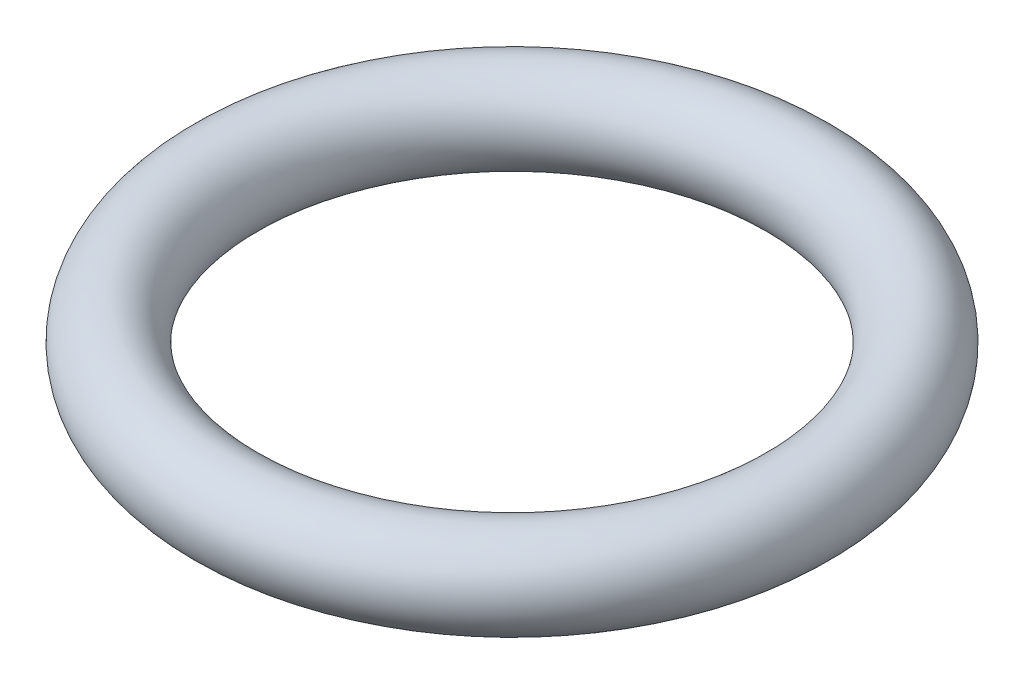
SolidWorks part; units mm, degrees
ref_plane "Front Plane" through (0, 0, 0) normal (0, 0, 1) x (1, 0, 0)
ref_plane "Top Plane" through (0, 0, 0) normal (0, 1, 0) x (1, 0, 0)
ref_plane "Right Plane" through (0, 0, 0) normal (1, 0, 0) x (0, 0, -1)
sketch "Sketch1" plane through (0, 0, 0) normal (0, 0, 1) x (1, 0, 0)
  line L0 (0, -3.9721) -> (0, 8.9728) construction
  circle A0 centre (-5.5, 0) radius 0.85
  dimension "D1" = 1.7
  dimension "D2" = 5.5
revolve "Revolve1" add sketch "Sketch1" angle 360 about L0
sketch "Sketch2" plane through (0, 0, 0) normal (0, 1, 0) x (1, 0, 0)
  circle A0 centre (0, 0) radius 0.323
